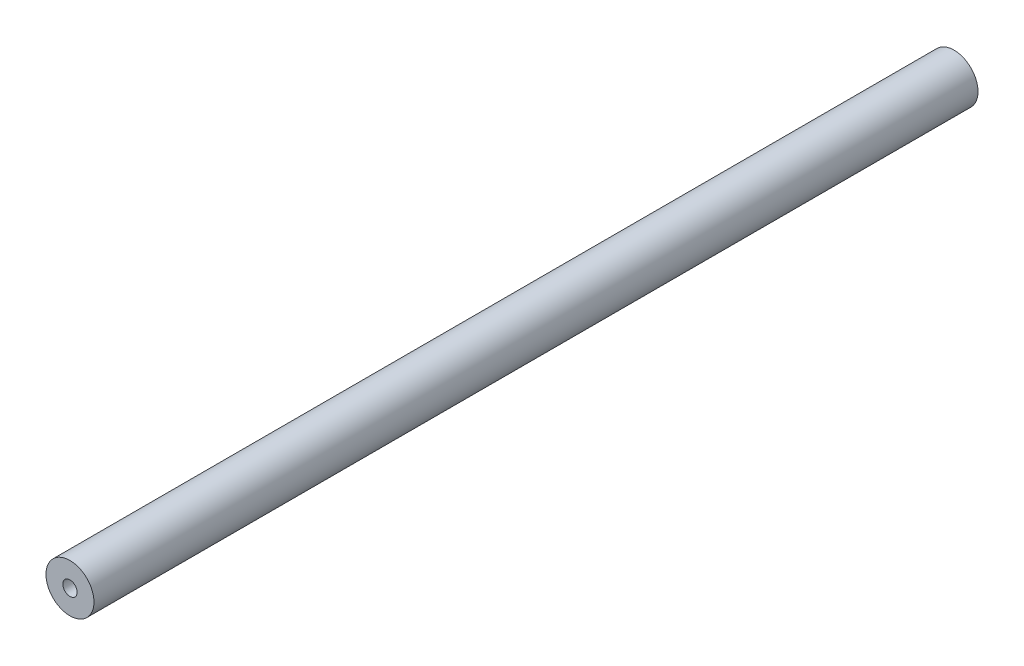
SolidWorks part; units mm, degrees
ref_plane "Alzado" through (0, 0, 0) normal (0, 0, 1) x (1, 0, 0)
ref_plane "Planta" through (0, 0, 0) normal (0, 1, 0) x (1, 0, 0)
ref_plane "Vista lateral" through (0, 0, 0) normal (1, 0, 0) x (0, 0, -1)
sketch "Sketch1" plane through (0, 0, 0) normal (0, 0, 1) x (1, 0, 0)
  line L0 (134.3, 77.7) -> (-12.7, 77.7) construction
  line L1 (116.35, 90.7) -> (116.35, 77.7) construction
  circle A0 centre (110, 84.05) radius 6.35
  dimension "D1" = 12.7
extrude "Boss-Extrude1" add sketch "Sketch1" against normal up to surface (233.9 mm away)
sketch "Sketch2" plane through (0, 0, 0) normal (0, 0, 1) x (1, 0, 0)
  point P0 (110, 84.05)
hole_wizard "#10-24 Tapped Hole1" positions "Sketch4" profile "Sketch3" tap size "#10-24" standard "ANSI Inch"
sketch "Sketch4" plane through (0, 0, 0) normal (0, 0, 1) x (1, 0, 0)
  point P0 (110, 84.05)
sketch "Sketch3" plane through (110, 84.05, 0) normal (1, 0, 0) x (0, -1, 0)
  line L0 (0, 0) -> (0, 13.9708)
  line L1 (0, 13.9708) -> (1.8986, 12.83)
  line L2 (1.8986, 12.83) -> (1.8986, 0)
  line L5 (1.8986, 0) -> (0, 0)
  line L10 (0, 13.9708) -> (-1.8987, 12.83) construction
  line L11 (0, -6.35) -> (0, 107.95) construction
  dimension "Tap Drill Dia." = 3.7973
  dimension "Tap Drill Depth" = 12.83
  dimension "Drill Angle" = 118
cosmetic thread "Hole Thread1" parameters "D1"=9.65, "D2"=4.826
sketch "Sketch5" plane through (0, 0, -233.9) normal (0, 0, -1) x (-1, 0, 0)
  point P0 (-110, 84.05)
hole_wizard "#10-24 Tapped Hole2" positions "Sketch7" profile "Sketch6" tap size "#10-24" standard "ANSI Inch"
sketch "Sketch7" plane through (0, 0, -233.9) normal (0, 0, -1) x (-1, 0, 0)
  point P0 (-110, 84.05)
sketch "Sketch6" plane through (110, 84.05, -233.9) normal (1, 0, 0) x (0, 1, 0)
  line L0 (0, 0) -> (0, 13.9708)
  line L1 (0, 13.9708) -> (1.8986, 12.83)
  line L2 (1.8986, 12.83) -> (1.8986, 0)
  line L5 (1.8986, 0) -> (0, 0)
  line L10 (0, 13.9708) -> (-1.8986, 12.83) construction
  line L11 (0, -6.35) -> (0, 107.95) construction
  dimension "Tap Drill Dia." = 3.7973
  dimension "Tap Drill Depth" = 12.83
  dimension "Drill Angle" = 118
cosmetic thread "Hole Thread2" parameters "D1"=9.65, "D2"=4.826
